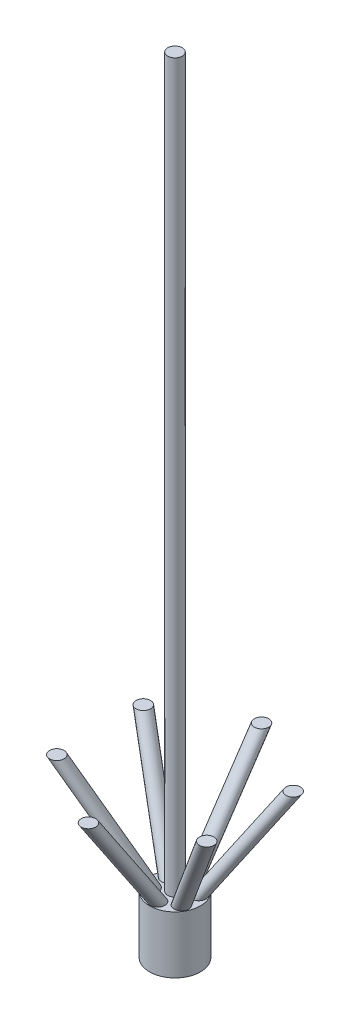
SolidWorks part; units mm, degrees
ref_plane "Front Plane" through (0, 0, 0) normal (0, 0, 1) x (1, 0, 0)
ref_plane "Top Plane" through (0, 0, 0) normal (0, 1, 0) x (1, 0, 0)
ref_plane "Right Plane" through (0, 0, 0) normal (1, 0, 0) x (0, 0, -1)
sketch "Sketch1" plane through (0, 0, 0) normal (0, 1, 0) x (1, 0, 0)
  circle A0 centre (0, 0) radius 0.4445
extrude "Boss-Extrude1" add sketch "Sketch1" along normal blind 1
sketch "Sketch2" plane through (0, 1, 0) normal (0, 1, 0) x (1, 0, 0)
  circle A0 centre (0, 0) radius 0.127
extrude "Boss-Extrude2" add sketch "Sketch2" along normal blind 12.7
sketch "Sketch3" plane through (0, 1, 0) normal (0, 1, 0) x (1, 0, 0)
  circle A0 centre (0, 0.3048) radius 0.127
  dimension "D1" = 0.3048
sketch3d "3DSketch1"
  line L0 (0, 1, -0.3048) -> (0, 2.7899, -1.5121)
  line L1 (0, 1.0095, -0.3048) -> (0, 50001.0095, -0.3048) construction
  dimension "D1" = 34
sweep "Sweep2" add profiles "Sketch3" path "3DSketch1"
pattern_circular "CirPattern1" count 6 over 360 about axis through (0, 1, 0) along (0, 1, 0) of "Sweep2"
